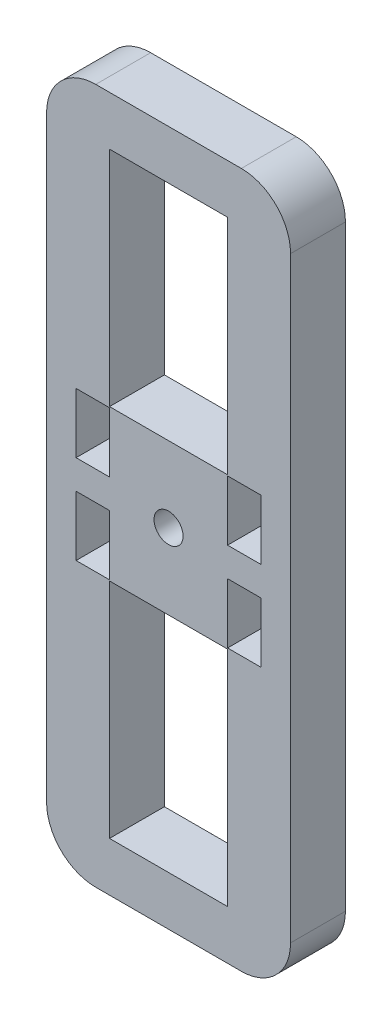
SolidWorks part; units mm, degrees
material "Acrylic (Medium-high impact)"
ref_plane "Front Plane" through (0, 0, 0) normal (0, 0, 1) x (1, 0, 0)
ref_plane "Top Plane" through (0, 0, 0) normal (0, 1, 0) x (1, 0, 0)
ref_plane "Right Plane" through (0, 0, 0) normal (1, 0, 0) x (0, 0, -1)
sketch "Sketch1" plane through (0, 0, 0) normal (0, 0, 1) x (1, 0, 0)
  line L0 (709.6957, 498.2947) -> (721.6957, 498.2947)
  line L1 (721.6957, 498.2947) -> (721.6957, 475.6297)
  line L2 (721.6957, 475.6297) -> (709.6957, 475.6297)
  line L3 (709.6957, 475.6297) -> (709.6957, 498.2947)
  line L4 (715.6957, 432.6147) -> (723.0957, 432.6147)
  line L5 (715.6957, 503.2947) -> (708.2957, 503.2947)
  line L6 (715.6957, 503.2947) -> (723.0957, 503.2947)
  line L7 (715.6957, 460.2797) -> (715.6957, 475.6297) construction
  line L8 (709.6957, 498.2947) -> (703.2957, 498.2947) construction
  line L9 (721.6957, 498.2947) -> (728.0957, 498.2947) construction
  line L10 (709.6957, 475.5297) -> (706.2957, 475.5297)
  line L11 (728.0957, 498.2947) -> (728.0957, 437.6147)
  line L12 (709.6957, 475.5297) -> (709.6957, 469.4297)
  line L13 (709.6957, 469.4297) -> (706.2957, 469.4297)
  line L14 (706.2957, 469.4297) -> (706.2957, 475.5297)
  line L15 (703.2957, 498.2947) -> (703.2957, 437.6147)
  line L16 (721.6957, 475.5297) -> (725.0957, 475.5297)
  line L17 (725.0957, 469.4297) -> (725.0957, 475.5297)
  line L18 (721.6957, 469.4297) -> (725.0957, 469.4297)
  line L19 (721.6957, 475.5297) -> (721.6957, 469.4297)
  line L20 (721.6957, 460.3797) -> (725.0957, 460.3797)
  line L21 (725.0957, 466.4797) -> (725.0957, 460.3797)
  line L22 (715.6957, 432.6147) -> (708.2957, 432.6147)
  line L23 (-284.3043, 443.4547) -> (49715.6957, 443.4547) construction
  line L24 (721.6957, 466.4797) -> (725.0957, 466.4797)
  line L25 (721.6957, 460.3797) -> (721.6957, 466.4797)
  line L26 (709.6957, 460.3797) -> (706.2957, 460.3797)
  line L27 (706.2957, 466.4797) -> (706.2957, 460.3797)
  line L28 (709.6957, 466.4797) -> (706.2957, 466.4797)
  line L29 (709.6957, 460.3797) -> (709.6957, 466.4797)
  line L30 (-282.9616, 469.4297) -> (49717.0384, 469.4297) construction
  line L31 (-282.9616, 466.4797) -> (49717.0384, 466.4797) construction
  line L37 (709.6957, 460.2797) -> (709.6957, 437.6147)
  line L38 (721.6957, 460.2797) -> (709.6957, 460.2797)
  line L39 (721.6957, 437.6147) -> (721.6957, 460.2797)
  line L40 (709.6957, 437.6147) -> (721.6957, 437.6147)
  line L171 (-296.4722, 467.9547) -> (49703.5278, 467.9547) construction
  circle A0 centre (715.6957, 467.9547) radius 1.475
  arc A1 (708.2957, 432.6147) -> (703.2957, 437.6147) centre (708.2957, 437.6147) cw
  arc A2 (708.2957, 503.2947) -> (703.2957, 498.2947) centre (708.2957, 498.2947) ccw
  arc A3 (723.0957, 503.2947) -> (728.0957, 498.2947) centre (723.0957, 498.2947) cw
  arc A4 (723.0957, 432.6147) -> (728.0957, 437.6147) centre (723.0957, 437.6147) ccw
  point P6 (715.6957, 504.6992)
  point P33 (715.6957, 475.6297)
  point P37 (715.6957, 467.9547)
  point P46 (715.6957, 431.2102)
  dimension "D4" = 2.95
  dimension "D2" = 3.4
  dimension "D1" = 6.1
  dimension "D7" = 3
  dimension "D3" = 0.1
  dimension "D8" = 5
  dimension "D6" = 5.84
  dimension "D5" = 24.5
extrude "Boss-Extrude1" add sketch "Sketch1" along normal blind 5.58
equation "\"D6@Sketch1\"=\"Servo_boss_radius@Servo-1.Part\""
equation "\"D5@Sketch1\"=\"Thigh_bottom_half_length@Thigh_bottom-1.Part\""
